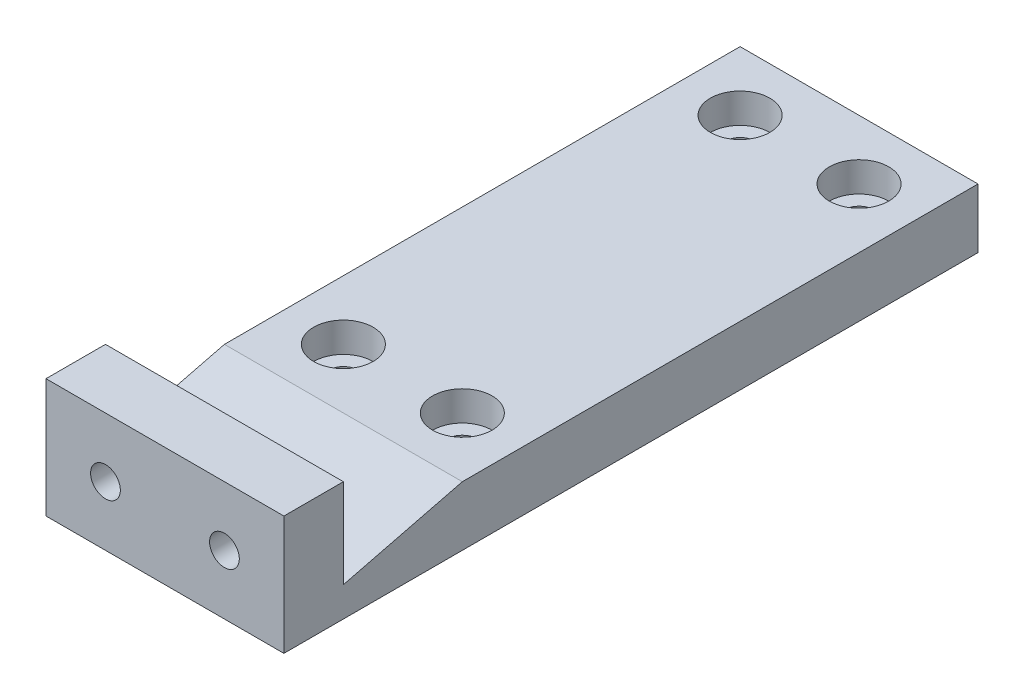
SolidWorks part; units mm, degrees
ref_plane "Front Plane" through (0, 0, 0) normal (0, 0, 1) x (1, 0, 0)
ref_plane "Top Plane" through (0, 0, 0) normal (0, 1, 0) x (1, 0, 0)
ref_plane "Right Plane" through (0, 0, 0) normal (1, 0, 0) x (0, 0, -1)
other "Configuration Table"
sketch "Sketch1" plane through (0, 0, 0) normal (0, 1, 0) x (1, 0, 0)
  line L1 (20, -58.35) -> (-20, -58.35)
  line L2 (20, -58.35) -> (20, 58.35)
  line L3 (20, 58.35) -> (-20, 58.35)
  line L4 (-20, -58.35) -> (-20, 58.35)
  line L5 (20, -58.35) -> (-20, 58.35) construction
  line L6 (20, 58.35) -> (-20, -58.35) construction
  point P0 (0, 0)
  dimension "D1" = 116.7
  dimension "D2" = 40
extrude "Boss-Extrude1" add sketch "Sketch1" along normal blind 10
sketch "Sketch2" plane through (0, 10, 0) normal (0, 1, 0) x (1, 0, 0)
  line L0 (-20, 58.35) -> (-20, -58.35) construction
  line L1 (-20, -48.35) -> (20, -48.35)
  line L2 (-20, -48.35) -> (-20, -58.35)
  line L3 (-20, -58.35) -> (20, -58.35)
  line L4 (20, -48.35) -> (20, -58.35)
  dimension "D1" = 10
extrude "Boss-Extrude2" add sketch "Sketch2" along normal blind 10
sketch "Sketch3" plane through (0, 10, 0) normal (0, 1, 0) x (1, 0, 0)
  line L0 (0, -48.35) -> (0, 58.35) construction
  line L1 (20, -48.35) -> (-20, -48.35) construction
  line L2 (20, 58.35) -> (-20, 58.35) construction
  line L3 (-20, 58.35) -> (-20, -48.35) construction
  line L4 (20, -48.35) -> (20, 58.35) construction
  circle A0 centre (-10, 48.35) radius 2.5
  circle A1 centre (10, 48.35) radius 2.5
  circle A2 centre (10, -18.35) radius 2.5
  circle A3 centre (-10, -18.35) radius 2.5
  dimension "D1" = 5
  dimension "D2" = 5
  dimension "D3" = 5
  dimension "D4" = 5
  dimension "D5" = 10
  dimension "D6" = 10
  dimension "D7" = 10
  dimension "D8" = 10
  dimension "D9" = 10
  dimension "D10" = 10
  dimension "D11" = 30
  dimension "D12" = 30
extrude "Cut-Extrude1" cut sketch "Sketch3" against normal through all both and the other way through all
sketch "Sketch4" plane through (0, 10, 0) normal (0, 1, 0) x (1, 0, 0)
  circle A0 centre (10, 48.35) radius 5
  circle A1 centre (-10, 48.35) radius 5
  circle A2 centre (10, -18.35) radius 5
  circle A3 centre (-10, -18.35) radius 5
extrude "Cut-Extrude2" cut sketch "Sketch4" against normal blind 5
sketch "Sketch5" plane through (-20, 0, 0) normal (-1, 0, 0) x (0, 0, 1)
  line L0 (28.35, 10) -> (48.35, 5)
  line L1 (-58.35, 10) -> (48.35, 10) construction
  line L2 (48.35, 5) -> (48.35, 10)
  line L3 (48.35, 10) -> (28.35, 10)
  line L4 (-58.35, 0) -> (58.35, 0) construction
  dimension "D1" = 5
  dimension "D2" = 20
extrude "Cut-Extrude3" cut sketch "Sketch5" against normal through all both and the other way through all
sketch "Sketch6" plane through (0, 0, 48.35) normal (0, 0, -1) x (-1, 0, 0)
  line L0 (0, 0) -> (0, 20) construction
  line L1 (-20, 20) -> (20, 20) construction
  line L2 (-20, 10) -> (20, 10) construction
  circle A0 centre (-10, 10) radius 2.5
  circle A1 centre (10, 10) radius 2.5
  dimension "D1" = 10
  dimension "D2" = 10
extrude "Cut-Extrude4" cut sketch "Sketch6" against normal through all
sketch "Sketch7" plane through (0, 0, 48.35) normal (0, 0, -1) x (-1, 0, 0)
  circle A0 centre (-10, 10) radius 5
  circle A1 centre (10, 10) radius 5
extrude "Cut-Extrude5" cut sketch "Sketch7" against normal blind 5
